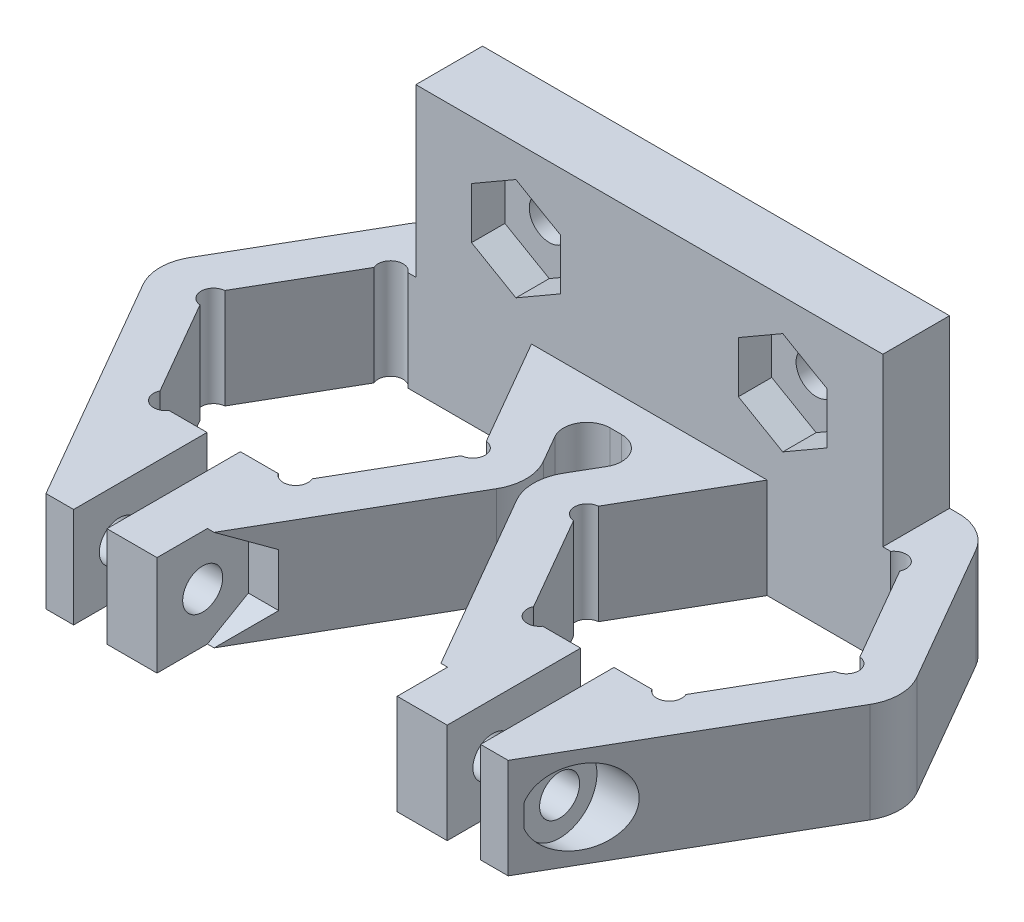
SolidWorks part; units mm, degrees
ref_plane "Front Plane" through (0, 0, 0) normal (0, 0, 1) x (1, 0, 0)
ref_plane "Top Plane" through (0, 0, 0) normal (0, 1, 0) x (1, 0, 0)
ref_plane "Right Plane" through (0, 0, 0) normal (1, 0, 0) x (0, 0, -1)
sketch "Sketch1" plane through (0, 0, 0) normal (0, 1, 0) x (1, 0, 0)
  line L0 (-1035.8141, -1.5875) -> (48964.1859, -1.5875) construction
  line L1 (-23.096, 16.129) -> (0, 16.129)
  line L3 (-21.9961, -25.654) -> (-19.3675, -25.654)
  line L5 (0, -1000) -> (0, 49000) construction
  line L7 (-1038.1, 0) -> (48961.9, 0) construction
  line L8 (-5.3396, -0.4019) -> (-11.2175, 9.779)
  line L9 (-11.2175, 9.779) -> (-22.9734, 9.779)
  line L10 (-25.027, 8.5934) -> (-30.2204, -0.4019)
  line L11 (-30.2204, -2.7731) -> (-25.027, -11.7684)
  line L12 (-22.9734, -12.954) -> (-19.3675, -12.954)
  line L13 (-10.533, -11.7684) -> (-5.3396, -2.7731)
  line L20 (-34.6077, -3.81) -> (-21.9961, -25.654)
  line L21 (-11.43, -21.958) -> (-0.9523, -3.81)
  line L25 (-26.9454, 13.9065) -> (-34.6077, 0.635)
  line L27 (-16.1925, -12.954) -> (-12.5866, -12.954)
  line L29 (-19.3675, -12.8426) -> (-19.3675, -25.654)
  line L31 (-16.1925, -12.8426) -> (-16.1925, -25.654)
  line L32 (-16.1925, -25.654) -> (-11.43, -25.654)
  line L33 (-17.78, -1001.5875) -> (-17.78, 48998.4125) construction
  line L34 (0, 16.129) -> (0, 6.604)
  line L35 (-0.549, 6.604) -> (0, 6.604)
  line L36 (-2.4737, 3.2702) -> (-0.9523, 0.635)
  line L37 (-11.43, -21.958) -> (-11.43, -25.654)
  circle A0 centre (-17.78, -1.5875) radius 11.3665 construction
  arc A1 (-23.096, 16.129) -> (-26.9454, 13.9065) centre (-23.096, 11.684) ccw
  arc A2 (-34.6077, -3.81) -> (-34.6077, 0.635) centre (-30.7583, -1.5875) cw
  circle A3 centre (-30.1112, -1.5875) radius 1.1906 construction
  circle A4 centre (-23.9456, 9.0916) radius 1.1906 construction
  circle A6 centre (-5.4488, -1.5875) radius 1.1906 construction
  circle A7 centre (-11.6144, -12.2666) radius 1.1906 construction
  circle A8 centre (-23.9456, -12.2666) radius 1.1906 construction
  arc A9 (-30.2204, -2.7731) -> (-30.2204, -0.4019) centre (-30.1112, -1.5875) cw
  arc A10 (-25.027, 8.5934) -> (-22.9734, 9.779) centre (-23.9456, 9.0916) cw
  arc A12 (-5.3396, -0.4019) -> (-5.3396, -2.7731) centre (-5.4488, -1.5875) cw
  arc A13 (-10.533, -11.7684) -> (-12.5866, -12.954) centre (-11.6144, -12.2666) cw
  arc A14 (-22.9734, -12.954) -> (-25.027, -11.7684) centre (-23.9456, -12.2666) cw
  arc A15 (-0.9523, 0.635) -> (-0.9523, -3.81) centre (-4.8017, -1.5875) cw
  arc A16 (-2.4737, 3.2702) -> (-0.549, 6.604) centre (-0.549, 4.3815) cw
  arc A17 (-12.5866, 9.779) -> (-10.533, 8.5934) centre (-11.6144, 9.0916) cw [skipped]
  circle A18 centre (-11.6144, 9.0916) radius 1.1906 construction
  point P0 (0, 0)
  point P47 (-17.78, -1.5875)
  point P71 (-17.78, -1.5875)
  dimension "D10" = 2.3813
  dimension "D15" = 4.445
  dimension "D18" = 4.445
  dimension "D20" = 2.2225
  dimension "D3" = 22.733
  dimension "D7" = 1.5875
  dimension "D8" = 4.318
  dimension "D9" = 4.318
  dimension "D2" = 17.78
  dimension "D14" = 12.7
  dimension "D4" = 3.175
  dimension "D5" = 1.5875
  dimension "D6" = 12.3312
  dimension "D13" = 4.318
  dimension "D17" = 4.318
  dimension "D19" = 9.525
  dimension "D21" = 4.7625
  dimension "D16" = 6.35
  dimension "D11" = 6
  dimension "D12" = 6
extrude "Boss-Extrude1" add sketch "Sketch1" along normal blind 9.525
sketch "Sketch2" plane through (0, 9.525, 0) normal (0, 1, 0) x (1, 0, 0)
  line L1 (0, 16.129) -> (-22.225, 16.129)
  line L2 (0, 16.129) -> (0, 9.779)
  line L3 (0, 9.779) -> (-22.225, 9.779)
  line L4 (-22.225, 16.129) -> (-22.225, 9.779)
  dimension "D1" = 22.225
  dimension "D2" = 6.35
extrude "Boss-Extrude2" add sketch "Sketch2" along normal blind 15.875
sketch "Sketch3" plane through (0, 0, -9.779) normal (0, 0, 1) x (1, 0, 0)
  line L0 (-1000, 17.4625) -> (49000, 17.4625) construction
  line L1 (0, 25.4) -> (0, 9.525) construction
  line L3 (-8.4772, 15.0245) -> (-8.4772, 19.9005)
  line L4 (-8.4772, 19.9005) -> (-12.7, 22.3385)
  line L5 (-12.7, 22.3385) -> (-16.9228, 19.9005)
  line L6 (-16.9228, 19.9005) -> (-16.9228, 15.0245)
  line L7 (-16.9228, 15.0245) -> (-12.7, 12.5865)
  line L8 (-12.7, 12.5865) -> (-8.4772, 15.0245)
  circle A0 centre (-12.7, 17.4625) radius 4.2227 construction
  point P5 (0, 17.4625)
  dimension "D1" = 8.4455
  dimension "D2" = 12.7
extrude "Cut-Extrude1" cut sketch "Sketch3" against normal blind 3.175
sketch "Sketch4" plane through (0, 0, -12.954) normal (0, 0, 1) x (1, 0, 0)
  line L0 (-16.9228, 19.9005) -> (-8.4772, 15.0245) construction
  line L2 (-12.7, 22.3385) -> (-12.7, 12.5865) construction
  line L4 (-8.4772, 19.9005) -> (-16.9228, 15.0245) construction
  circle A0 centre (-12.7, 17.4625) radius 1.905
  dimension "D1" = 3.81
extrude "Cut-Extrude2" cut sketch "Sketch4" against normal through all
ref_plane "Plane1" through (-11.43, 0, 0) normal (-1, 0, 0) x (0, 0, 1)
sketch "Sketch5" plane through (-11.43, 0, 0) normal (-1, 0, 0) x (0, 0, 1)
  line L0 (-977.521, 4.7625) -> (49022.479, 4.7625) construction
  line L1 (25.654, 9.525) -> (25.654, 0) construction
  line L2 (21.3043, -994.9584) -> (21.3043, 49005.0416) construction
  line L3 (21.3043, 9.7852) -> (28.0616, 9.7852)
  line L4 (21.3043, 9.7852) -> (16.9545, 7.2738)
  line L5 (16.9545, 7.2738) -> (16.9545, 2.2512)
  line L6 (16.9545, 2.2512) -> (21.3043, -0.2602)
  line L7 (21.3043, -0.2602) -> (25.654, 2.2512) construction
  line L8 (25.654, 2.2512) -> (25.654, 7.2738) construction
  line L9 (25.654, 7.2738) -> (21.3043, 9.7852) construction
  line L10 (28.0616, 9.7852) -> (28.0616, -0.2602)
  line L11 (28.0616, -0.2602) -> (21.3043, -0.2602)
  circle A0 centre (21.3043, 4.7625) radius 4.3498 construction
  point P5 (25.654, 4.7625)
  dimension "D1" = 8.6995
extrude "Cut-Extrude4" cut sketch "Sketch5" against normal through all
sketch "Sketch6" plane through (-11.43, 0, 0) normal (1, 0, 0) x (0, 0, -1)
  line L0 (-16.9545, 7.2738) -> (-21.3043, 4.7625) construction
  line L1 (-21.3043, 4.7625) -> (-16.9545, 2.2512) construction
  line L3 (-16.9545, 7.2738) -> (-16.9545, 2.2512) construction
  circle A0 centre (-21.3043, 4.7625) radius 1.905
  dimension "D2" = 3.81
  dimension "D1" = 60
extrude "Cut-Extrude5" cut sketch "Sketch6" against normal through all
ref_plane "Plane2" through (-22.5425, 0, 0) normal (1, 0, 0) x (0, 0, -1)
sketch "Sketch7" plane through (-22.5425, 0, 0) normal (1, 0, 0) x (0, 0, -1)
  circle A2 centre (-21.3043, 4.7625) radius 1.905 construction
  circle A3 centre (-21.3043, 4.7625) radius 1.905 construction
  circle A4 centre (-21.3043, 4.7625) radius 3.556
  dimension "D1" = 7.112
extrude "Cut-Extrude6" cut sketch "Sketch7" against normal through all
sketch "Sketch9" plane through (0, 25.4, 0) normal (0, 1, 0) x (1, 0, 0)
  line L0 (-22.225, 9.779) -> (0, 9.779) construction
  line L1 (0, 16.129) -> (-6.35, 16.129)
  line L2 (0, 16.129) -> (0, 9.779)
  line L3 (0, 9.779) -> (-6.35, 9.779)
  line L4 (-6.35, 16.129) -> (-6.35, 9.779)
  dimension "D1" = 6.35
extrude "Boss-Extrude3" [suppressed] add sketch "Sketch9" along normal blind 31.75
sketch "Sketch10" [suppressed] plane through (0, 0, -9.779) normal (0, 0, 1) x (1, 0, 0)
  line L0 (0, 50.8) -> (0, 31.75) construction
  line L1 (0, 57.15) -> (0, 9.525) construction
  line L3 (-1.8987, 50.8) -> (-1.8987, 31.75)
  line L4 (-22.225, 25.4) -> (-6.35, 25.4) construction
  line L5 (-6.35, 57.15) -> (0, 57.15) construction
  line L6 (0, 52.6987) -> (0, 29.8514)
  arc A0 (0, 52.6987) -> (-1.8987, 50.8) centre (0, 50.8) ccw
  arc A1 (-1.8987, 31.75) -> (0, 29.8514) centre (0, 31.75) ccw
  point P4 (0, 44.45)
  dimension "D1" = 1.8986
  dimension "D2" = 6.35
  dimension "D3" = 6.35
extrude "Cut-Extrude8" [suppressed] cut sketch "Sketch10" against normal through all
sketch "Sketch12" [suppressed] plane through (0, 0, -16.129) normal (0, 0, -1) x (-1, 0, 0)
  line L0 (6.35, 48.7246) -> (14.2875, 25.4)
  line L1 (6.35, 57.15) -> (6.35, 25.4) construction
  line L2 (6.35, 25.4) -> (22.225, 25.4) construction
rib "Rib1" [suppressed] sketch "Sketch12" sketch "Sketch12" thickness 3.175 extrusion direction parallel to sketch draft on no parameters "D1"=3.175
mirror "Mirror1" about plane through (0, 9.525, 0) normal (1, 0, 0) of bodies 108
equation "\"D5@Sketch1\"=\"D4@Sketch1\"/2"
equation "\"D13@Sketch1\"=\"D8@Sketch1\""
equation "\"D9@Sketch1\"=\"D8@Sketch1\""
equation "\"D18@Sketch1\"=\"D15@Sketch1\""
equation "\"D20@Sketch1\"=\"D15@Sketch1\"/2"
